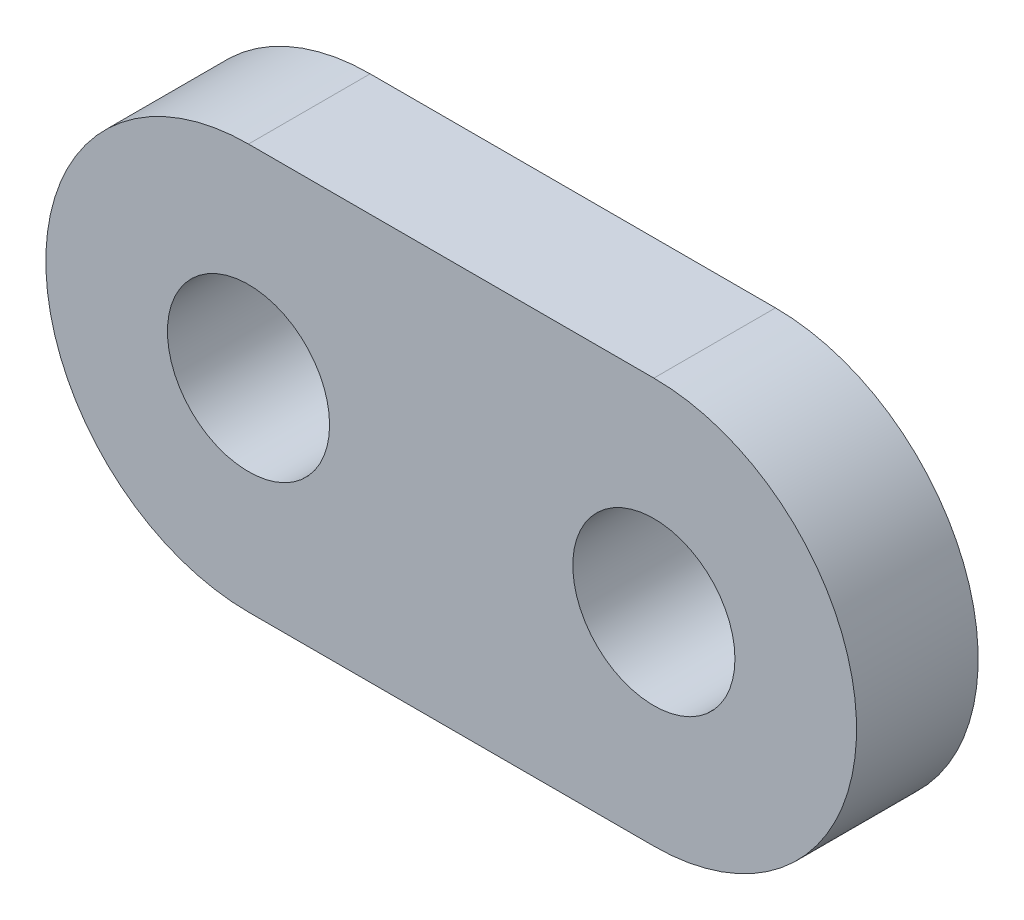
SolidWorks part; units mm, degrees
ref_plane "Front Plane" through (0, 0, 0) normal (0, 0, 1) x (1, 0, 0)
ref_plane "Top Plane" through (0, 0, 0) normal (0, 1, 0) x (1, 0, 0)
ref_plane "Right Plane" through (0, 0, 0) normal (1, 0, 0) x (0, 0, -1)
sketch "Sketch1" plane through (0, 0, 0) normal (0, 0, 1) x (1, 0, 0)
  line L0 (-13.4024, 0) -> (-3.4024, 0) construction
  line L1 (-13.4024, -5) -> (-3.4024, -5)
  line L2 (-13.4024, 5) -> (-3.4024, 5)
  circle A0 centre (-13.4024, 0) radius 2
  circle A1 centre (-3.4024, 0) radius 2
  arc A2 (-13.4024, -5) -> (-13.4024, 5) centre (-13.4024, 0) cw
  arc A3 (-3.4024, -5) -> (-3.4024, 5) centre (-3.4024, 0) ccw
  dimension "D1" = 4
  dimension "D4" = 10
  dimension "D2" = 5
  dimension "D3" = 5
extrude "Boss-Extrude1" add sketch "Sketch1" along normal blind 3
